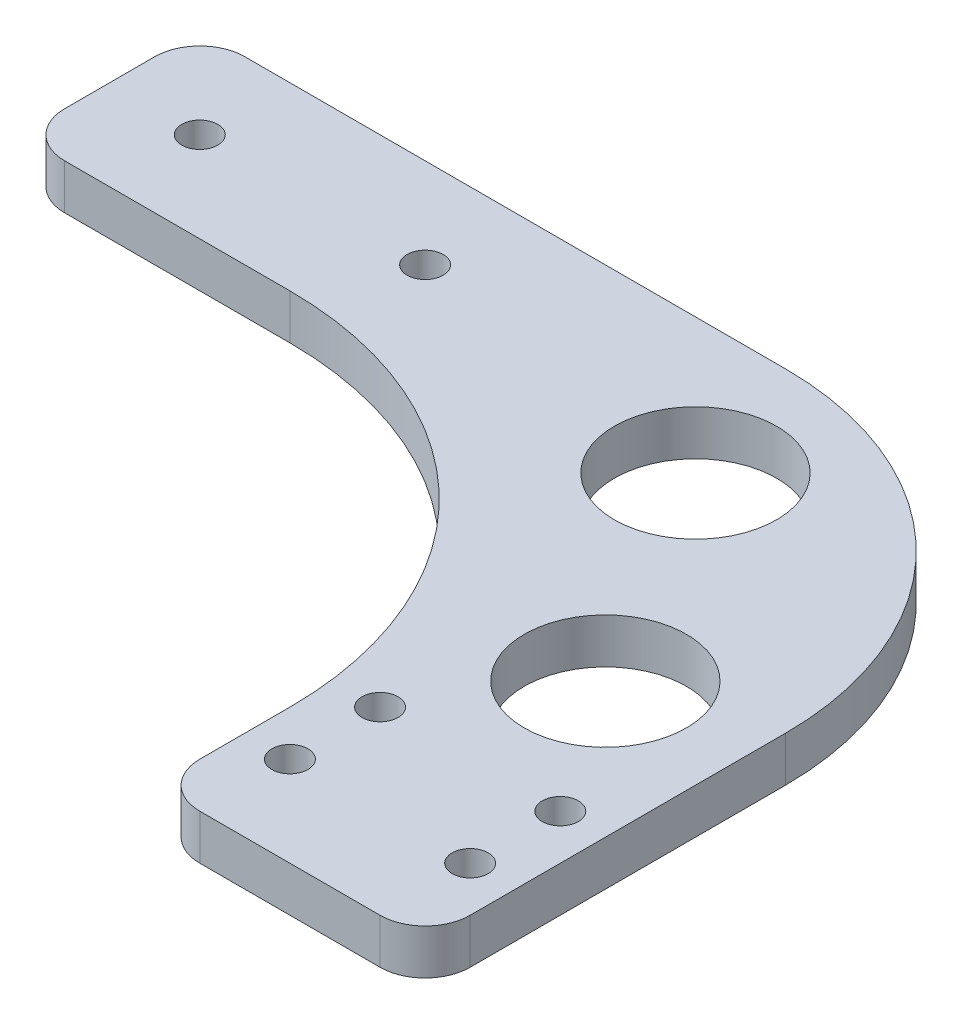
SolidWorks part; units mm, degrees
ref_plane "前视基准面" through (0, 0, 0) normal (0, 0, 1) x (1, 0, 0)
ref_plane "上视基准面" through (0, 0, 0) normal (0, 1, 0) x (1, 0, 0)
ref_plane "右视基准面" through (0, 0, 0) normal (1, 0, 0) x (0, 0, -1)
other "质心 (COM)"
sketch "草图1" plane through (0, 0, 0) normal (0, 1, 0) x (1, 0, 0)
  line L0 (-89.625, 35.375) -> (10.375, 35.375)
  line L1 (10.375, 35.375) -> (10.375, -39.625)
  line L2 (10.375, -39.625) -> (-19.625, -39.625)
  line L3 (-19.625, -39.625) -> (-19.625, 15.375)
  line L4 (-19.625, 15.375) -> (-89.625, 15.375)
  line L5 (-89.625, 15.375) -> (-89.625, 35.375)
  dimension "D1" = 30
  dimension "D2" = 20
  dimension "D3" = 100
  dimension "D4" = 55
extrude "凸台-拉伸1" add sketch "草图1" along normal blind 5
fillet "圆角1" radius 40 1 edges at (-19.625, 2.5, -15.375)
fillet "圆角2" radius 5 4 edges at (10.375, 2.5, 39.625) (-19.625, 2.5, 39.625) (-89.625, 2.5, -35.375) (-89.625, 2.5, -15.375)
sketch "草图2" plane through (0, 5, 0) normal (0, 1, 0) x (1, 0, 0)
  line L0 (-19.625, -24.625) -> (-19.625, -34.625) construction
  line L1 (10.375, -34.625) -> (10.375, 35.375) construction
  line L2 (-14.625, -39.625) -> (5.375, -39.625) construction
  circle A0 centre (-14.625, -29.625) radius 2
  circle A1 centre (5.375, -29.625) radius 2
  circle A2 centre (5.375, -19.625) radius 2
  circle A3 centre (-14.625, -19.625) radius 2
  dimension "D1" = 5
  dimension "D2" = 5
  dimension "D3" = 5
  dimension "D4" = 5
  dimension "D5" = 10
  dimension "D6" = 10
  dimension "D7" = 10
  dimension "D8" = 10
  dimension "D9" = 4
  dimension "D10" = 4
  dimension "D11" = 4
  dimension "D12" = 4
extrude "切除-拉伸1" cut sketch "草图2" against normal blind 5
fillet "圆角3" radius 35 1 edges at (10.375, 2.5, -35.375)
sketch "草图3" plane through (0, 5, 0) normal (0, 1, 0) x (1, 0, 0)
  line L0 (10.375, -34.625) -> (10.375, 0.375) construction
  line L1 (-14.625, -39.625) -> (5.375, -39.625) construction
  circle A0 centre (-19.625, 20.375) radius 9
  circle A1 centre (-4.625, -4.625) radius 9
  dimension "D1" = 18
  dimension "D2" = 15
  dimension "D3" = 35
  dimension "D4" = 18
  dimension "D5" = 30
  dimension "D6" = 60
extrude "切除-拉伸2" cut sketch "草图3" against normal through all
sketch "草图4" plane through (0, 5, 0) normal (0, 1, 0) x (1, 0, 0)
  line L0 (-24.625, 35.375) -> (-84.625, 35.375) construction
  line L1 (-89.625, 30.375) -> (-89.625, 20.375) construction
  circle A0 centre (-79.625, 25.375) radius 2
  circle A1 centre (-54.625, 25.375) radius 2
  point P8 (-89.625, 25.375)
  dimension "D1" = 25
  dimension "D2" = 10
  dimension "D3" = 10
  dimension "D4" = 4
  dimension "D5" = 4
  dimension "D6" = 10
extrude "切除-拉伸3" cut sketch "草图4" against normal through all
